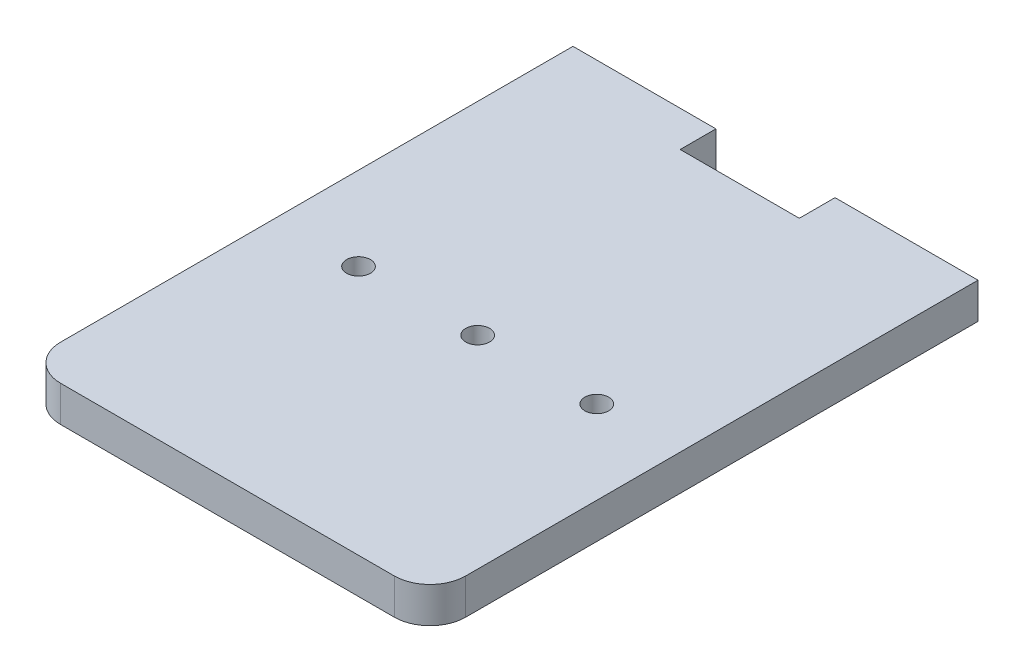
SolidWorks part; units mm, degrees
ref_plane "Plan de face" through (0, 0, 0) normal (0, 0, 1) x (1, 0, 0)
ref_plane "Plan de dessus" through (0, 0, 0) normal (0, 1, 0) x (1, 0, 0)
ref_plane "Plan de droite" through (0, 0, 0) normal (1, 0, 0) x (0, 0, -1)
sketch "Esquisse1" plane through (0, 0, 0) normal (0, 1, 0) x (1, 0, 0)
  line L0 (-5, 46) -> (-5, 43)
  line L1 (-14, 0) -> (14, 0)
  line L2 (-17, 3) -> (-17, 46)
  line L3 (-17, 46) -> (-5, 46)
  line L4 (17, 3) -> (17, 46)
  line L5 (-5, 43) -> (5, 43)
  line L6 (5, 43) -> (5, 46)
  line L7 (5, 46) -> (17, 46)
  line L8 (0, 0) -> (0, 43) construction
  line L9 (-10, 21) -> (10, 21) construction
  circle A0 centre (0, 21) radius 1
  circle A1 centre (-10, 21) radius 1
  circle A2 centre (10, 21) radius 1
  arc A3 (14, 0) -> (17, 3) centre (14, 3) ccw
  arc A4 (-14, 0) -> (-17, 3) centre (-14, 3) cw
  point P4 (0, 0)
  point P12 (0, 43)
  point P17 (0, 21)
  point P22 (17, 0)
  dimension "D5" = 21
  dimension "D7" = 2
  dimension "D8" = 3
  dimension "D1" = 34
  dimension "D2" = 46
  dimension "D3" = 10
  dimension "D4" = 3
  dimension "D6" = 20
extrude "Boss.-Extru.1" add sketch "Esquisse1" along normal blind 3
